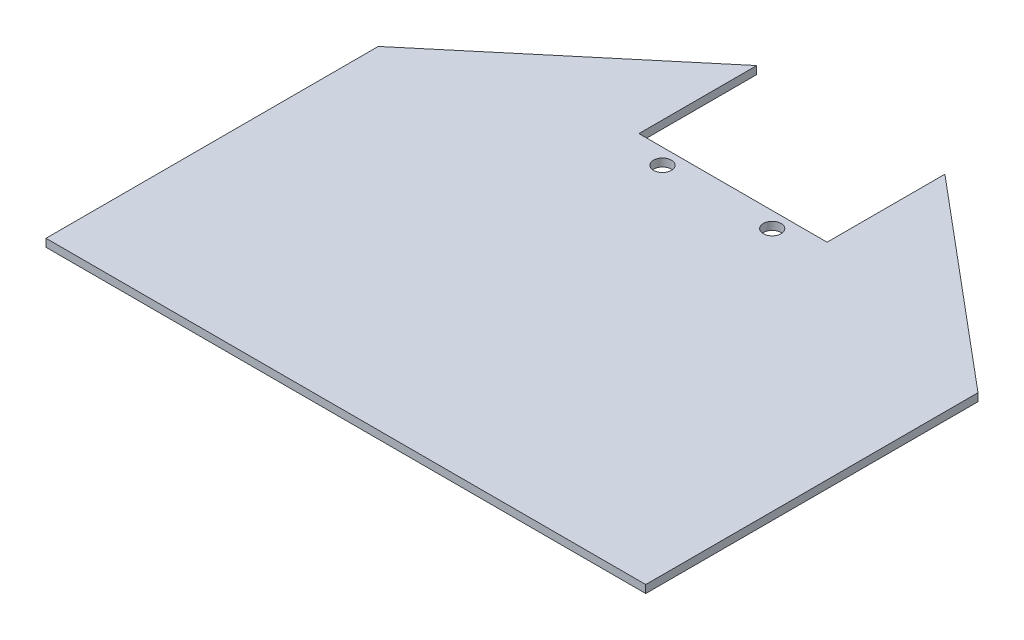
SolidWorks part; units mm, degrees
ref_plane "前视基准面" through (0, 0, 0) normal (0, 0, 1) x (1, 0, 0)
ref_plane "上视基准面" through (0, 0, 0) normal (0, 1, 0) x (1, 0, 0)
ref_plane "右视基准面" through (0, 0, 0) normal (1, 0, 0) x (0, 0, -1)
sketch "草图1" plane through (0, 0, 0) normal (0, 1, 0) x (1, 0, 0)
  line L0 (-76.5, 42.3821) -> (0, 106.5732)
  line L2 (-76.5, 42.3821) -> (-76.5, -42.3821)
  line L3 (-76.5, -42.3821) -> (76.5, -42.3821)
  line L4 (76.5, 42.3821) -> (76.5, -42.3821)
  line L5 (0, -42.3821) -> (0, 173.0527) construction
  line L6 (-76.5, 0) -> (76.5, 0) construction
  line L7 (0, 106.5732) -> (76.5, 42.3821)
  point P0 (0, 0)
  dimension "D1" = 153
  dimension "D2" = 40
extrude "凸台-拉伸1" add sketch "草图1" along normal blind 2
sketch "草图2" plane through (0, 2, 0) normal (0, 1, 0) x (1, 0, 0)
  line L0 (0, 106.5732) -> (0, -42.3821) construction
  line L1 (-76.5, -42.3821) -> (76.5, -42.3821) construction
  line L2 (-76.5, 42.3821) -> (76.5, 42.3821) construction
  line L4 (-24, 56.3821) -> (24, 56.3821)
  line L5 (-24, 56.3821) -> (-24, 106.5732)
  line L6 (-24, 106.5732) -> (24, 106.5732)
  line L7 (24, 56.3821) -> (24, 106.5732)
  line L8 (0, 106.5732) -> (0, 56.3821) construction
  line L9 (-24, 81.4776) -> (24, 81.4776) construction
  point P9 (0, 81.4776)
  point P13 (0, 107.1094)
  dimension "D1" = 48
  dimension "D2" = 14
extrude "切除-拉伸1" cut sketch "草图2" against normal blind 10
sketch "草图3" plane through (0, 2, 0) normal (0, 1, 0) x (1, 0, 0)
  line L0 (0, 104.8378) -> (0, -42.3821) construction
  line L1 (-76.5, -42.3821) -> (76.5, -42.3821) construction
  line L2 (-24, 56.3821) -> (24, 56.3821) construction
  circle A0 centre (14, 52.3821) radius 2.275
  circle A1 centre (-14, 52.3821) radius 2.275
  dimension "D1" = 28
  dimension "D2" = 4.55
  dimension "D3" = 4
extrude "切除-拉伸2" cut sketch "草图3" against normal blind 10
